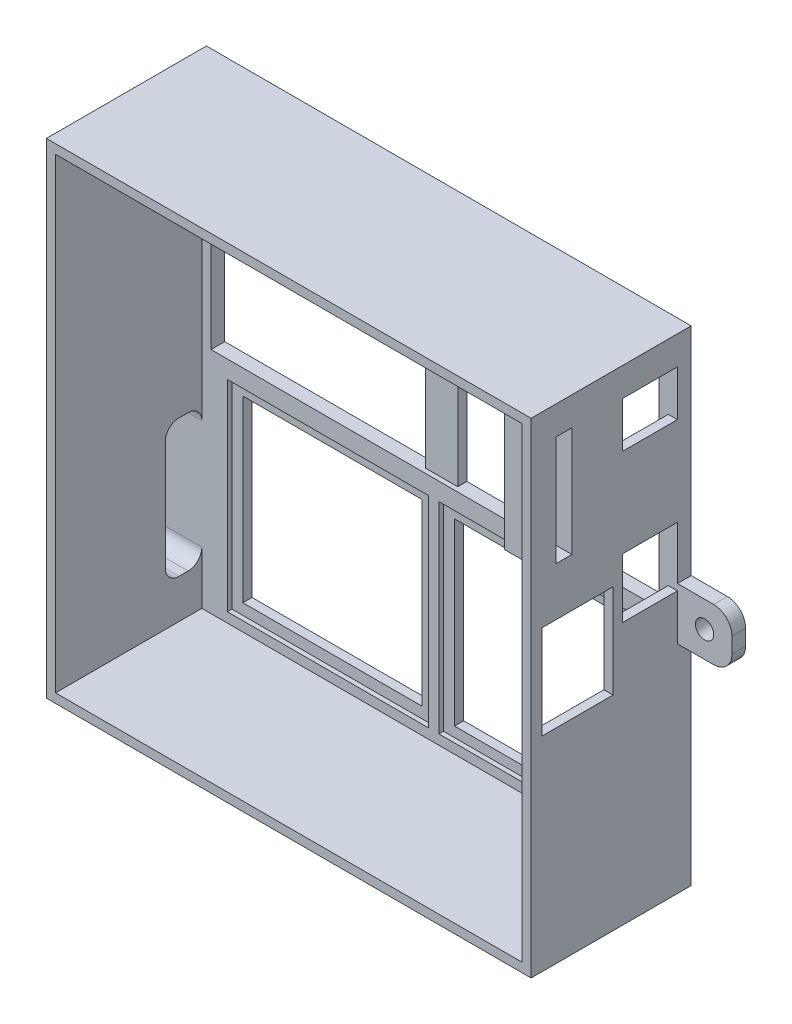
SolidWorks part; units mm, degrees
ref_plane "前视基准面" through (0, 0, 0) normal (0, 0, 1) x (1, 0, 0)
ref_plane "上视基准面" through (0, 0, 0) normal (0, 1, 0) x (1, 0, 0)
ref_plane "右视基准面" through (0, 0, 0) normal (1, 0, 0) x (0, 0, -1)
sketch "草图1" plane through (0, 0, 0) normal (0, 0, 1) x (1, 0, 0)
  line L0 (-56.9609, 55.7891) -> (49.0391, 55.7891)
  line L1 (-54.9609, 53.7891) -> (47.0391, 53.7891)
  line L2 (-54.9609, 53.7891) -> (-54.9609, -0.2109)
  line L3 (-54.9609, -0.2109) -> (47.0391, -0.2109)
  line L4 (47.0391, 53.7891) -> (47.0391, -0.2109)
  line L5 (49.0391, 55.7891) -> (49.0391, -2.2109)
  line L7 (-56.9609, 55.7891) -> (-56.9609, -2.2109)
  line L9 (-54.9609, -4.2109) -> (-10.9609, -4.2109)
  line L10 (-54.9609, -4.2109) -> (-54.9609, -48.2109)
  line L11 (-54.9609, -48.2109) -> (-10.9609, -48.2109)
  line L12 (-10.9609, -4.2109) -> (-10.9609, -48.2109)
  line L14 (-56.9609, -50.2109) -> (-8.9609, -50.2109)
  line L15 (-56.9609, -2.2109) -> (-56.9609, -50.2109)
  line L16 (-56.9609, -2.2109) -> (49.0391, -2.2109) construction
  line L17 (-56.9609, -2.2109) -> (-8.9609, -2.2109) construction
  line L18 (-8.9609, -50.2109) -> (49.0391, -50.2109)
  line L19 (49.0391, -50.2109) -> (49.0391, -2.2109)
  line L21 (-8.9609, -2.2109) -> (-8.9609, -50.2109) construction
  dimension "D1" = 102
  dimension "D2" = 54
  dimension "D4" = 44
  dimension "D5" = 44
  dimension "D6" = 2
  dimension "D3" = 2
extrude "凸台-拉伸1" add sketch "草图1" along normal blind 5
sketch "草图2" plane through (0, 0, 0) normal (0, 0, -1) x (-1, 0, 0)
  line L0 (56.9609, 55.7891) -> (56.9609, -50.2109) construction
  line L1 (-49.0391, 55.7891) -> (56.9609, 55.7891)
  line L2 (-49.0391, 55.7891) -> (-49.0391, -2.199)
  line L3 (-49.0391, -2.199) -> (56.9609, -2.199)
  line L4 (56.9609, 55.7891) -> (56.9609, -2.199)
  line L5 (-45.0391, 1.801) -> (52.9609, 1.801)
  line L6 (9.1336, -2.199) -> (56.9609, -2.199)
  line L7 (9.1336, -2.199) -> (9.1336, -50.2109)
  line L8 (9.1336, -50.2109) -> (56.9609, -50.2109)
  line L9 (56.9609, -2.199) -> (56.9609, -50.2109)
  line L10 (-45.0391, 51.7891) -> (-45.0391, 1.801)
  line L11 (-45.0391, 51.7891) -> (52.9609, 51.7891)
  line L12 (52.9609, 51.7891) -> (52.9609, 1.801)
  line L13 (52.9609, -6.199) -> (52.9609, -46.2109)
  line L14 (13.1336, -46.2109) -> (52.9609, -46.2109)
  line L15 (13.1336, -6.199) -> (13.1336, -46.2109)
  line L16 (13.1336, -6.199) -> (52.9609, -6.199)
  line M3 (54.9609, 53.7891) -> (54.9609, -0.2109)
  line M4 (54.9609, -0.2109) -> (-47.0391, -0.2109)
  line M5 (-47.0391, -0.2109) -> (-47.0391, 53.7891)
  line M6 (-47.0391, 53.7891) -> (54.9609, 53.7891)
  line M11 (54.9609, -4.2109) -> (54.9609, -48.2109)
  line M12 (54.9609, -48.2109) -> (10.9609, -48.2109)
  line M13 (10.9609, -48.2109) -> (10.9609, -4.2109)
  line M14 (10.9609, -4.2109) -> (54.9609, -4.2109)
  dimension "D1" = 4
  dimension "D2" = 4
extrude "凸台-拉伸2" add sketch "草图2" against normal blind 3 contours L11 L12 L5 L10 M3 M6 M5 M4 | L15 L16 L13 L14 M11 M14 M13 M12
sketch "草图3" plane through (0, 0, 5) normal (0, 0, 1) x (1, 0, 0)
  line L0 (-54.9609, 53.7891) -> (47.0391, 53.7891)
  line L1 (-56.9609, 55.7891) -> (49.0391, 55.7891)
  line L2 (-56.9609, 55.7891) -> (-56.9609, -50.2109)
  line L3 (-56.9609, -50.2109) -> (49.0391, -50.2109)
  line L4 (49.0391, 55.7891) -> (49.0391, -50.2109)
  line L5 (47.0391, 53.7891) -> (47.0391, -48.2109)
  line L6 (-54.9609, -48.2109) -> (47.0391, -48.2109)
  line L7 (-54.9609, 53.7891) -> (-54.9609, -48.2109)
  dimension "D1" = 2
extrude "凸台-拉伸3" add sketch "草图3" along normal blind 30
sketch "草图4" plane through (49.0391, 0, 0) normal (1, 0, 0) x (0, 0, -1)
  line L0 (-3, -0.2109) -> (-3, 53.7891) construction
  line L2 (-3, 49.5312) -> (-3, 39.5312)
  line L4 (-15, 49.5312) -> (-15, 39.5312)
  line L5 (-15, 49.5312) -> (-3, 49.5312)
  line L7 (-15, 7.1085) -> (-3, 7.1085)
  line L9 (-15, 20.1085) -> (-15, 7.1085)
  line L10 (-15, 39.5312) -> (-3, 39.5312)
  line L12 (-15, 20.1085) -> (-3, 20.1085)
  line L15 (-3, 20.1085) -> (-3, 7.1085)
  dimension "D1" = 13
  dimension "D2" = 10
  dimension "D3" = 12
extrude "切除-拉伸1" cut sketch "草图4" against normal blind 30
sketch "草图5" plane through (0, 0, 5) normal (0, 0, 1) x (1, 0, 0)
  line L1 (-3.1288, -46.0657) -> (40.8712, -46.0657)
  line L2 (-3.1288, -46.0657) -> (-3.1288, -2.0657)
  line L3 (-3.1288, -2.0657) -> (40.8712, -2.0657)
  line L4 (40.8712, -46.0657) -> (40.8712, -2.0657)
  dimension "D1" = 44
  dimension "D2" = 44
extrude "切除-拉伸2" cut sketch "草图5" against normal blind 3
sketch "草图6" plane through (0, 0, 2) normal (0, 0, 1) x (1, 0, 0)
  line L1 (-0.708, -4.6234) -> (38.9671, -4.6234)
  line L2 (-0.708, -4.6234) -> (-0.708, -43.8718)
  line L3 (-0.708, -43.8718) -> (38.9671, -43.8718)
  line L4 (38.9671, -4.6234) -> (38.9671, -43.8718)
extrude "切除-拉伸3" cut sketch "草图6" against normal through all
sketch "草图8" plane through (0, 0, 0) normal (0, 0, -1) x (-1, 0, 0)
  line L0 (-45.0391, 51.7891) -> (52.9609, 51.7891) construction
  line L1 (13.1336, -6.199) -> (52.9609, -6.199)
  line L2 (13.1336, -6.199) -> (13.1336, -46.2109)
  line L3 (13.1336, -46.2109) -> (52.9609, -46.2109)
  line L4 (52.9609, -6.199) -> (52.9609, -46.2109)
  line L5 (0, 51.7891) -> (7.1072, 51.7891)
  line L6 (0, 51.7891) -> (0, 1.801)
  line L7 (0, 1.801) -> (7.1072, 1.801)
  line L8 (7.1072, 51.7891) -> (7.1072, 1.801)
  line L9 (-45.0391, 1.801) -> (52.9609, 1.801) construction
extrude "凸台-拉伸5" add sketch "草图8" against normal blind 2
sketch "草图9" plane through (0, 0, 3) normal (0, 0, 1) x (1, 0, 0)
  line L1 (-54.9609, -4.2109) -> (-10.9609, -4.2109)
  line L2 (-54.9609, -4.2109) -> (-54.9609, -48.2109)
  line L3 (-54.9609, -48.2109) -> (-10.9609, -48.2109)
  line L4 (-10.9609, -4.2109) -> (-10.9609, -48.2109)
extrude "凸台-拉伸6" add sketch "草图9" along normal blind 2 and the other way blind 3
sketch "草图10" plane through (0, 0, 5) normal (0, 0, 1) x (1, 0, 0)
  line L1 (-49.4008, -2.0657) -> (-5.4008, -2.0657)
  line L2 (-49.4008, -2.0657) -> (-49.4008, -46.0657)
  line L3 (-49.4008, -46.0657) -> (-5.4008, -46.0657)
  line L4 (-5.4008, -2.0657) -> (-5.4008, -46.0657)
  point P4 (-5.8274, -2.277)
  point P5 (-5.4008, -2.0657)
  dimension "D1" = 44
  dimension "D2" = 44
extrude "切除-拉伸5" cut sketch "草图10" against normal blind 3
sketch "草图11" plane through (0, 0, 2) normal (0, 0, 1) x (1, 0, 0)
  line L1 (-46.9956, -4.5167) -> (-7.8538, -4.5167)
  line L2 (-46.9956, -4.5167) -> (-46.9956, -43.6585)
  line L3 (-46.9956, -43.6585) -> (-7.8538, -43.6585)
  line L4 (-7.8538, -4.5167) -> (-7.8538, -43.6585)
extrude "切除-拉伸6" cut sketch "草图11" against normal blind 3
sketch "草图12" plane through (49.0391, 0, 0) normal (1, 0, 0) x (0, 0, -1)
  line L1 (-30.7784, 53.7893) -> (-20.7784, 53.7893)
  line L2 (-30.7784, 53.7893) -> (-30.7784, 23.7893)
  line L3 (-30.7784, 23.7893) -> (-20.7784, 23.7893)
  line L4 (-20.7784, 53.7893) -> (-20.7784, 23.7893)
  dimension "D1" = 30
  dimension "D2" = 10
extrude "凸台-拉伸7" add sketch "草图12" against normal blind 10
sketch "草图13" plane through (49.0391, 0, 0) normal (1, 0, 0) x (0, 0, -1)
  line L1 (-29.5831, 49.5364) -> (-26.0831, 49.5364)
  line L2 (-29.5831, 49.5364) -> (-29.5831, 25.5364)
  line L3 (-29.5831, 25.5364) -> (-26.0831, 25.5364)
  line L4 (-26.0831, 49.5364) -> (-26.0831, 25.5364)
  dimension "D1" = 24
  dimension "D2" = 3.5
extrude "切除-拉伸7" cut sketch "草图13" against normal blind 20
sketch "草图14" plane through (0, 23.7893, 0) normal (0, -1, 0) x (1, 0, 0)
  line L0 (37.9069, 25.4724) -> (38.5432, 25.4724)
  line L1 (38.5432, 25.4724) -> (47.0391, 20.7784)
  line L2 (47.0391, 20.7784) -> (47.0391, 19.4002)
  line L3 (47.0391, 35) -> (47.0391, 5) construction
  line L4 (47.0391, 19.4002) -> (37.9069, 19.4002)
  line L5 (37.9069, 19.4002) -> (37.9069, 25.4724)
extrude "切除-拉伸8" cut sketch "草图14" against normal up to surface (29.9997 mm away) up to face at (19.5391, 53.7891, 22.3892)
sketch "草图15" plane through (49.0391, 0, 0) normal (1, 0, 0) x (0, 0, -1)
  line L1 (-32.5915, 14.9168) -> (-17.0915, 14.9168)
  line L2 (-32.5915, 14.9168) -> (-32.5915, -5.5832)
  line L3 (-32.5915, -5.5832) -> (-17.0915, -5.5832)
  line L4 (-17.0915, 14.9168) -> (-17.0915, -5.5832)
  dimension "D1" = 20.5
  dimension "D2" = 15.5
extrude "切除-拉伸9" cut sketch "草图15" against normal blind 30
sketch "草图18" plane through (0, 0, 5) normal (0, 0, 1) x (1, 0, 0)
  line L1 (-54.9609, -0.2109) -> (47.0391, -0.2109)
  line L2 (-54.9609, -0.2109) -> (-54.9609, -48.2109)
  line L3 (-54.9609, -48.2109) -> (47.0391, -48.2109)
  line L4 (47.0391, -0.2109) -> (47.0391, -48.2109)
extrude "切除-拉伸11" cut sketch "草图18" against normal blind 2
sketch "草图19" plane through (-54.9609, 0, 0) normal (1, 0, 0) x (0, 0, -1)
  line L0 (-3, -48.2109) -> (-3, 7.1085) construction
  line L1 (-8, -9.6361) -> (-6, -9.6361)
  line L2 (-11, -12.6361) -> (-11, -36.6361)
  line L3 (-8, -39.6361) -> (-6, -39.6361)
  line L4 (-3, -12.6361) -> (-3, -36.6361)
  arc A0 (-6, -9.6361) -> (-3, -12.6361) centre (-6, -12.6361) cw
  arc A1 (-3, -36.6361) -> (-6, -39.6361) centre (-6, -36.6361) cw
  arc A2 (-8, -39.6361) -> (-11, -36.6361) centre (-8, -36.6361) cw
  arc A3 (-8, -9.6361) -> (-11, -12.6361) centre (-8, -12.6361) ccw
  point P8 (-3, -9.6361)
  point P11 (-3, -39.6361)
  point P14 (-11, -39.6361)
  point P17 (-11, -9.6361)
  dimension "D3" = 3
  dimension "D1" = 8
  dimension "D2" = 30
extrude "切除-拉伸12" cut sketch "草图19" against normal through all
sketch "草图20" plane through (-56.9609, 0, 0) normal (-1, 0, 0) x (0, 0, 1)
  line L0 (0, 55.7891) -> (0, -50.2109) construction
  line L1 (0, -41.8454) -> (9.1805, -41.8454)
  line L2 (0, -41.8454) -> (0, -7.0764)
  line L3 (0, -7.0764) -> (9.1805, -7.0764)
  line L4 (13.1805, -37.8454) -> (13.1805, -11.0764)
  line L21 (3, 7.1085) -> (3, -48.2109)
  line L22 (3, -48.2109) -> (35, -48.2109)
  line L23 (35, -48.2109) -> (35, 53.7891)
  line L24 (35, 53.7891) -> (30.7784, 53.7891)
  line L25 (30.7784, 53.7891) -> (30.7784, 23.7893)
  line L26 (30.7784, 23.7893) -> (20.7784, 23.7893)
  line L27 (20.7784, 23.7893) -> (20.7784, 53.7891)
  line L28 (20.7784, 53.7891) -> (3, 53.7891)
  line L29 (3, 53.7891) -> (3, 49.5312)
  line L30 (3, 49.5312) -> (15, 49.5312)
  line L31 (15, 49.5312) -> (15, 39.5312)
  line L32 (15, 39.5312) -> (3, 39.5312)
  line L33 (3, 39.5312) -> (3, 20.1085)
  line L34 (3, 20.1085) -> (15, 20.1085)
  line L35 (15, 20.1085) -> (15, 7.1085)
  line L36 (15, 7.1085) -> (3, 7.1085)
  line L37 (3, 7.1085) -> (3, -48.2109)
  line L38 (3, -48.2109) -> (35, -48.2109)
  line L39 (35, -48.2109) -> (35, 53.7891)
  line L40 (35, 53.7891) -> (30.7784, 53.7891)
  line L41 (30.7784, 53.7891) -> (30.7784, 23.7893)
  line L42 (30.7784, 23.7893) -> (20.7784, 23.7893)
  line L43 (20.7784, 23.7893) -> (20.7784, 53.7891)
  line L44 (20.7784, 53.7891) -> (3, 53.7891)
  line L45 (3, 53.7891) -> (3, 49.5312)
  line L46 (3, 49.5312) -> (15, 49.5312)
  line L47 (15, 49.5312) -> (15, 39.5312)
  line L48 (15, 39.5312) -> (3, 39.5312)
  line L49 (3, 39.5312) -> (3, 20.1085)
  line L50 (3, 20.1085) -> (15, 20.1085)
  line L51 (15, 20.1085) -> (15, 7.1085)
  line L52 (15, 7.1085) -> (3, 7.1085)
  arc A0 (13.1805, -37.8454) -> (9.1805, -41.8454) centre (9.1805, -37.8454) cw
  arc A1 (9.1805, -7.0764) -> (13.1805, -11.0764) centre (9.1805, -11.0764) cw
  line M20 (3, -36.6361) -> (3, -12.6361)
  arc M21 (3, -12.6361) -> (6, -9.6361) centre (6, -12.6361) cw
  line M22 (6, -9.6361) -> (8, -9.6361)
  arc M23 (8, -9.6361) -> (11, -12.6361) centre (8, -12.6361) cw
  line M24 (11, -12.6361) -> (11, -36.6361)
  arc M25 (11, -36.6361) -> (8, -39.6361) centre (8, -36.6361) cw
  line M26 (8, -39.6361) -> (6, -39.6361)
  arc M27 (6, -39.6361) -> (3, -36.6361) centre (6, -36.6361) cw
  line M28 (0, 55.7891) -> (0, -50.2109)
  dimension "D1" = 4
  dimension "D2" = 0
extrude "凸台-拉伸10" add sketch "草图20" along normal blind 6 contours A1 L3 L37 L1 A0 L4 M21 M22 M23 M24 M25 M26 M27 | L37 L3 L1 M28 M20
sketch "草图21" plane through (0, 0, 0) normal (0, 0, -1) x (-1, 0, 0)
  line L0 (-49.0391, 2.7891) -> (49950.9609, 2.7891) construction
  line L1 (-49.0391, -50.2109) -> (-49.0391, 55.7891) construction
  line L2 (56.9609, 55.7891) -> (56.9609, -7.0764) construction
  line L3 (56.9609, -2.9169) -> (64.8733, -2.9169)
  line L4 (56.9609, -2.9169) -> (56.9609, 8.495)
  line L5 (56.9609, 8.495) -> (64.8733, 8.495)
  line L6 (68.8733, 1.0831) -> (68.8733, 4.495)
  line L7 (3.9609, 55.7891) -> (3.9609, -50.2109) construction
  line L8 (-49.0391, 55.7891) -> (56.9609, 55.7891) construction
  line L9 (56.9609, -50.2109) -> (-49.0391, -50.2109) construction
  line L10 (-60.9514, 1.0831) -> (-60.9514, 4.495)
  line L11 (-49.0391, 8.495) -> (-56.9514, 8.495)
  line L12 (-49.0391, -2.9169) -> (-49.0391, 8.495)
  line L13 (-49.0391, -2.9169) -> (-56.9514, -2.9169)
  circle A0 centre (62.9007, 2.7891) radius 2
  arc A1 (64.8733, 8.495) -> (68.8733, 4.495) centre (64.8733, 4.495) cw
  arc A2 (64.8733, -2.9169) -> (68.8733, 1.0831) centre (64.8733, 1.0831) ccw
  arc A3 (-56.9514, -2.9169) -> (-60.9514, 1.0831) centre (-56.9514, 1.0831) cw
  arc A4 (-56.9514, 8.495) -> (-60.9514, 4.495) centre (-56.9514, 4.495) ccw
  circle A5 centre (-54.9788, 2.7891) radius 2
  point P4 (-49.0391, 2.7891)
  dimension "D1" = 4
  dimension "D2" = 4
extrude "凸台-拉伸11" add sketch "草图21" against normal blind 3
